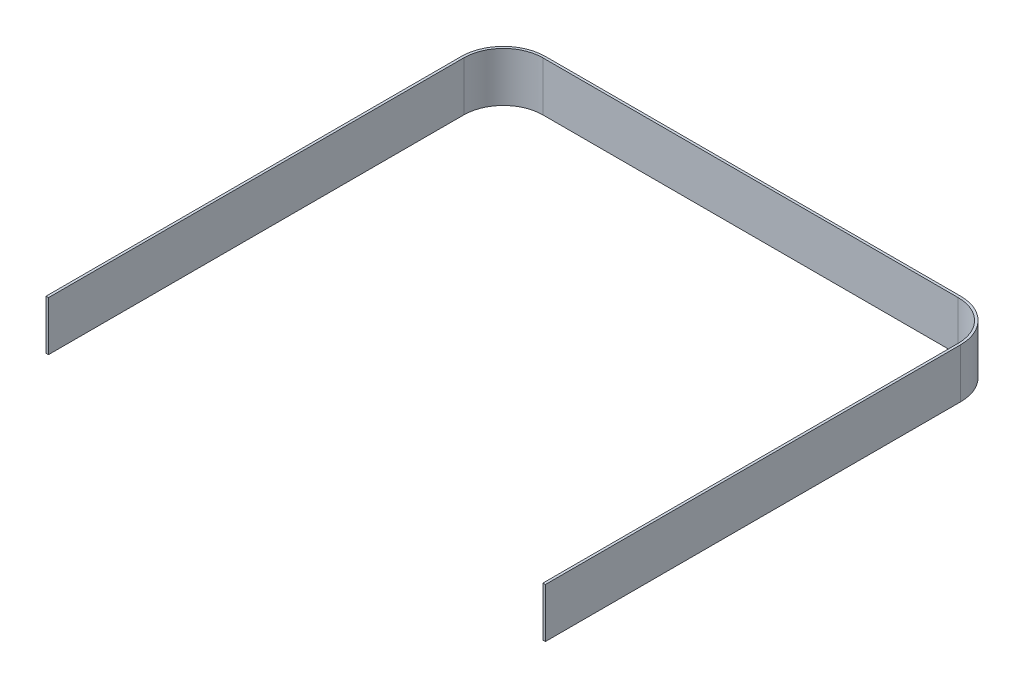
SolidWorks part; units mm, degrees
ref_plane "Front Plane" through (0, 0, 0) normal (0, 0, 1) x (1, 0, 0)
ref_plane "Top Plane" through (0, 0, 0) normal (0, 1, 0) x (1, 0, 0)
ref_plane "Right Plane" through (0, 0, 0) normal (1, 0, 0) x (0, 0, -1)
sketch "Sketch3" plane through (0, 0, 0) normal (0, 1, 0) x (1, 0, 0)
  line L0 (0, 0) -> (635, 0)
  line L1 (635, 0) -> (635, -584.2)
  line L2 (0, 0) -> (0, -584.2)
extrude "Extrude-Thin1" add sketch "Sketch3" along normal blind 63.5 thin thin type one direction wall 3.175
